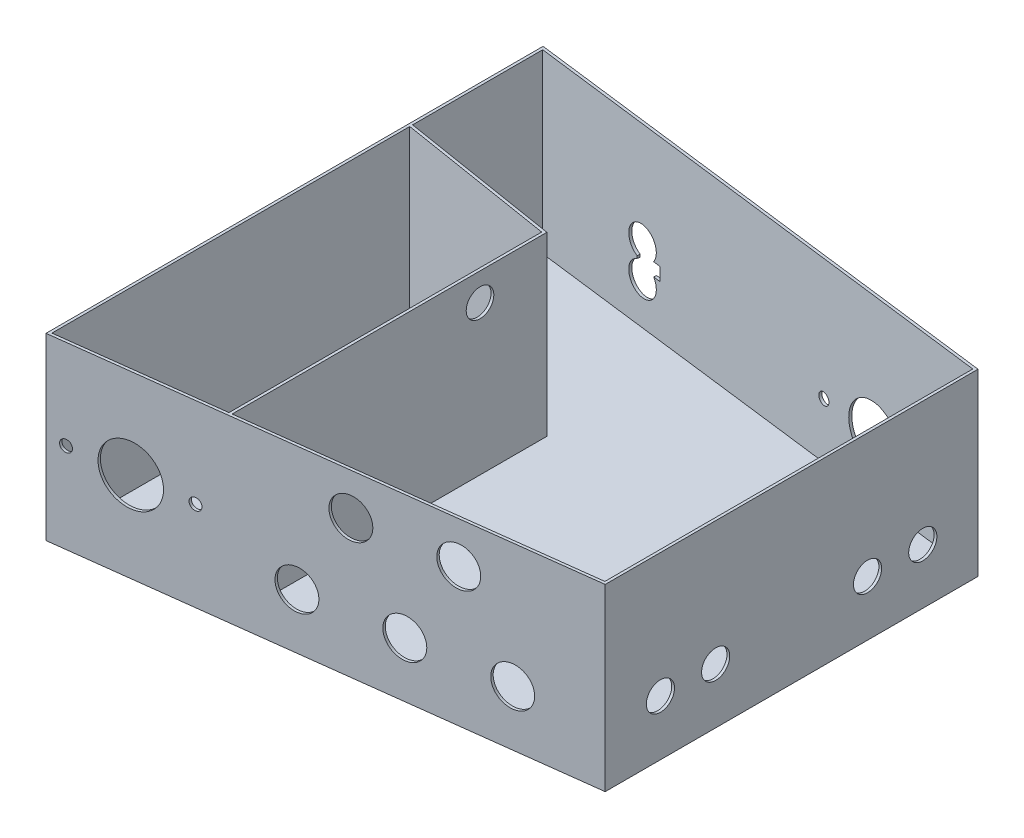
SolidWorks part; units mm, degrees
ref_plane "Front Plane" through (0, 0, 0) normal (0, 0, 1) x (1, 0, 0)
ref_plane "Top Plane" through (0, 0, 0) normal (0, 1, 0) x (1, 0, 0)
ref_plane "Right Plane" through (0, 0, 0) normal (1, 0, 0) x (0, 0, -1)
sketch "Sketch1" plane through (0, 0, 0) normal (0, 1, 0) x (1, 0, 0)
  line L0 (0, 0) -> (20, 0) construction
  line L8 (174.2857, -135) -> (174.2857, 135)
  line L11 (-185.7143, -180) -> (-185.7143, 180)
  line L12 (174.2857, 135) -> (-185.7143, 180)
  line L13 (-185.7143, -180) -> (174.2857, -135)
  line L14 (-185.7143, 180) -> (174.2857, -135) construction
  line L15 (174.2857, 135) -> (-185.7143, -180) construction
  point P0 (0, 0)
  point P1 (0, 0)
  point P3 (-0.1549, -0.2817)
  point P6 (0, 0)
  point P8 (-0.1549, -0.1401)
  point P11 (0, 0)
  dimension "D1" = 360
  dimension "D2" = 270
  dimension "D3" = 360
  dimension "D4" = 20
extrude "Boss-Extrude2" add sketch "Sketch1" along normal blind 2
sketch "Sketch2" plane through (0, 2, 0) normal (0, 1, 0) x (1, 0, 0)
  line L5 (174.2857, 135) -> (-185.7143, 180)
  line L6 (-185.7143, 180) -> (-185.7143, -180)
  line L10 (-185.7143, -180) -> (174.2857, -135)
  line L11 (174.2857, -135) -> (174.2857, 135)
  line L12 (172.2857, -133.2344) -> (172.2857, 133.2344)
  line L13 (172.2857, 133.2344) -> (-183.7143, 177.7344)
  line L14 (-183.7143, 177.7344) -> (-183.7143, -177.7344)
  line L15 (-183.7143, -177.7344) -> (172.2857, -133.2344)
  point P0 (0, 0)
  dimension "D1" = 2
extrude "Boss-Extrude3" add sketch "Sketch2" along normal blind 128 separate body
sketch "Sketch3" plane through (0, 2, 0) normal (0, 1, 0) x (1, 0, 0)
  line L0 (-67.7143, 51.4916) -> (-67.7143, -165.25)
  line L1 (-185.7143, -180) -> (174.2857, -135) construction
  line L2 (-67.7143, 51.4916) -> (-67.7143, 64.7312)
  line L3 (-67.7143, 64.7312) -> (-185.7143, 83.7889)
  line L4 (-185.7143, 180) -> (-185.7143, -180) construction
  line L5 (-69.7143, 51.4916) -> (-69.7143, -165.5)
  line L6 (-69.7143, 51.4916) -> (-69.7143, 63.0283)
  line L7 (-69.7143, 63.0283) -> (-185.7143, 81.763)
  line L8 (-185.7143, 83.7889) -> (-185.7143, 81.763)
  line L9 (-69.7143, 63.0283) -> (-186.0332, 81.8145) construction
  line L10 (-69.7143, -165.5) -> (-67.7143, -165.25)
  line L11 (-69.7143, 51.4916) -> (-69.7143, -165.25) construction
  dimension "D1" = 2
extrude "Boss-Extrude4" add sketch "Sketch3" along normal up to surface (128 mm away) up to face at (-5.7143, 130, 0)
sketch "Sketch4" plane through (19.2967, 0, 154.3736) normal (0.124, 0, 0.9923) x (0.9923, 0, -0.124)
  line L0 (-206.6064, 130) -> (-206.6064, 0) construction
  line L1 (-206.6064, 130) -> (156.1952, 130) construction
  line L2 (-206.6064, 0) -> (156.1952, 0) construction
  line L3 (156.1952, 130) -> (156.1952, 0) construction
  circle A0 centre (-151.6064, 65) radius 21.25
  circle A1 centre (-193.6064, 65) radius 4.2
  circle A2 centre (-109.6064, 65) radius 4.2
  circle A3 centre (-43.8048, 40) radius 14.25
  circle A4 centre (26.1952, 40) radius 14.25
  circle A6 centre (96.1952, 40) radius 14.25
  circle A7 centre (-8.8048, 100) radius 14.25
  circle A8 centre (61.1952, 100) radius 14.25
  point P20 (0, 0)
  point P21 (0, 0)
  dimension "D1" = 42.5
  dimension "D6" = 8.4
  dimension "D7" = 8.4
  dimension "D8" = 28.5
  dimension "D9" = 28.5
  dimension "D10" = 28.5
  dimension "D11" = 28.5
  dimension "D12" = 28.5
  dimension "D2" = 55
  dimension "D3" = 65
  dimension "D4" = 42
  dimension "D5" = 42
  dimension "D13" = 70
  dimension "D14" = 70
  dimension "D15" = 60
  dimension "D16" = 35
  dimension "D17" = 40
  dimension "D18" = 70
  dimension "D19" = 200
extrude "Cut-Extrude1" cut sketch "Sketch4" against normal up to surface (2 mm away) up to face at (-126.7143, 66, 170.6094)
sketch "Sketch5" plane through (174.2857, 0, 0) normal (1, 0, 0) x (0, 0, -1)
  line L0 (-135, 130) -> (-135, 0) construction
  line L1 (-135, 0) -> (135, 0) construction
  line L2 (135, 130) -> (135, 0) construction
  circle A0 centre (-95, 40) radius 10.2
  circle A1 centre (-55, 40) radius 10.2
  circle A2 centre (55, 40) radius 10.2
  circle A3 centre (95, 40) radius 10.2
  point P12 (0, 0)
  point P15 (0, 0)
  dimension "D6" = 20.4
  dimension "D7" = 20.4
  dimension "D8" = 20.4
  dimension "D9" = 20.4
  dimension "D1" = 40
  dimension "D2" = 40
  dimension "D3" = 40
  dimension "D4" = 40
  dimension "D5" = 40
extrude "Cut-Extrude2" cut sketch "Sketch5" against normal up to surface (2 mm away) up to face at (172.2857, 66, 0)
sketch "Sketch6" plane through (19.2967, 0, -154.3736) normal (0.124, 0, -0.9923) x (-0.9923, 0, -0.124)
  line L0 (-156.1952, 0) -> (206.6064, 0) construction
  line L1 (-156.1952, 130) -> (-156.1952, 0) construction
  line L2 (106.3754, 43.9178) -> (106.3754, 48.6678)
  line L3 (106.3754, 43.9178) -> (106.3754, 39.1678)
  line L4 (125.5754, 43.0008) -> (125.5754, 44.8347)
  line L6 (106.3754, 48.6678) -> (111.7648, 48.6678)
  line L8 (111.7648, 39.1678) -> (106.3754, 39.1678)
  circle A0 centre (-72.1952, 42) radius 21.25
  circle A1 centre (-114.1952, 42) radius 4.2
  circle A2 centre (-30.1952, 42) radius 4.2
  arc A3 (125.5754, 44.8347) -> (111.7648, 48.6678) centre (121.0754, 55.4178) ccw
  arc A4 (111.7648, 39.1678) -> (125.5754, 43.0008) centre (121.0754, 32.4178) ccw
  dimension "D1" = 8.4
  dimension "D2" = 8.4
  dimension "D3" = 42.5
  dimension "D8" = 23
  dimension "D9" = 23
  dimension "D4" = 42
  dimension "D5" = 42
  dimension "D6" = 42
  dimension "D7" = 42
  dimension "D10" = 23
  dimension "D11" = 4.75
  dimension "D12" = 4.75
  dimension "D13" = 4.5
  dimension "D14" = 14.7
extrude "Cut-Extrude3" cut sketch "Sketch6" against normal up to surface (2 mm away) up to face at (-5.7143, 66, -155.4844)
sketch "Sketch7" plane through (-69.7143, 0, 0) normal (-1, 0, 0) x (0, 0, 1)
  line L0 (-63.0283, 130) -> (163.4844, 130) construction
  circle A0 centre (-16.3336, 110) radius 10
  dimension "D1" = 20
  dimension "D2" = 20
extrude "Cut-Extrude4" cut sketch "Sketch7" against normal up to surface (2 mm away) up to face at (-67.7143, 66, 49.2516)
sketch "Sketch8" plane through (-185.7143, 0, 0) normal (-1, 0, 0) x (0, 0, 1)
  line L0 (-180, 0) -> (180, 0) construction
  line L1 (-180, 130) -> (-180, 0) construction
  circle A0 centre (-140, 40) radius 10
  dimension "D1" = 20
  dimension "D2" = 40
  dimension "D3" = 40
extrude "Cut-Extrude5" cut sketch "Sketch8" against normal up to surface (2 mm away) up to face at (-183.7143, 66, -130.6002)
